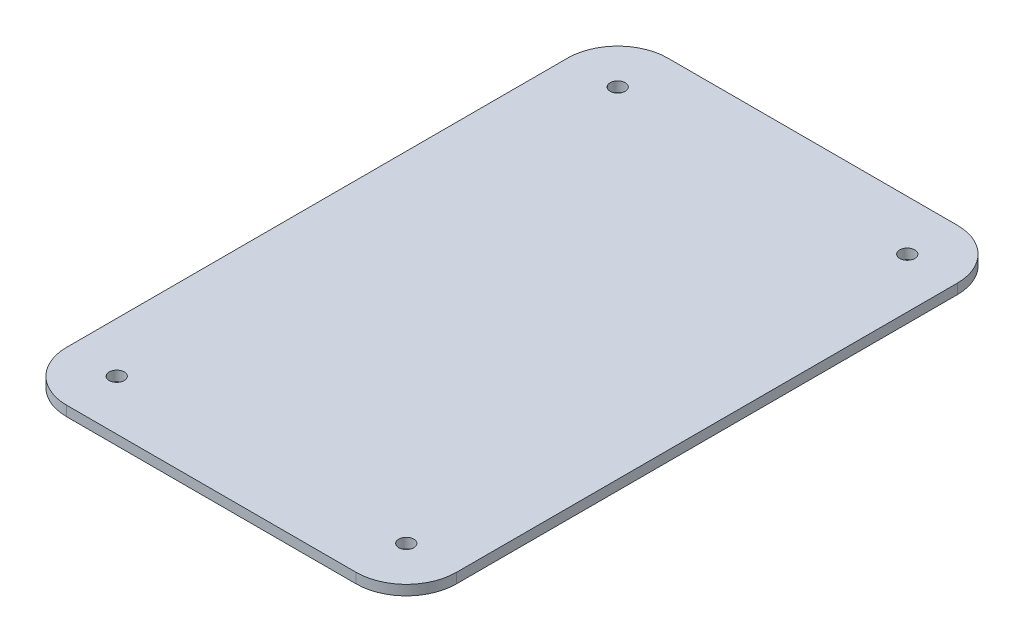
SolidWorks part; units mm, degrees
ref_plane "Front Plane" through (0, 0, 0) normal (0, 0, 1) x (1, 0, 0)
ref_plane "Top Plane" through (0, 0, 0) normal (0, 1, 0) x (1, 0, 0)
ref_plane "Right Plane" through (0, 0, 0) normal (1, 0, 0) x (0, 0, -1)
sketch "Sketch1" plane through (0, 0, 0) normal (0, 1, 0) x (1, 0, 0)
  line L1 (-43.3692, 87.0693) -> (34.4308, 87.0693)
  line L2 (-43.3692, 87.0693) -> (-43.3692, -32.9307)
  line L3 (-43.3692, -32.9307) -> (34.4308, -32.9307)
  line L4 (34.4308, 87.0693) -> (34.4308, -32.9307)
extrude "Boss-Extrude1" add sketch "Sketch1" along normal blind 2
fillet "Fillet1" radius 10 4 edges at (-43.3692, 1, -87.0693) (34.4308, 1, -87.0693) (34.4308, 1, 32.9307) (-43.3692, 1, 32.9307)
sketch "Sketch2" plane through (0, 2, 0) normal (0, 1, 0) x (1, 0, 0)
  circle A0 centre (-33.3692, -22.9307) radius 1.5
  circle A1 centre (24.4308, -22.9307) radius 1.5
  circle A2 centre (-33.3692, 77.0693) radius 1.5
  circle A3 centre (24.4308, 77.0693) radius 1.5
extrude "Cut-Extrude1" cut sketch "Sketch2" against normal blind 21
